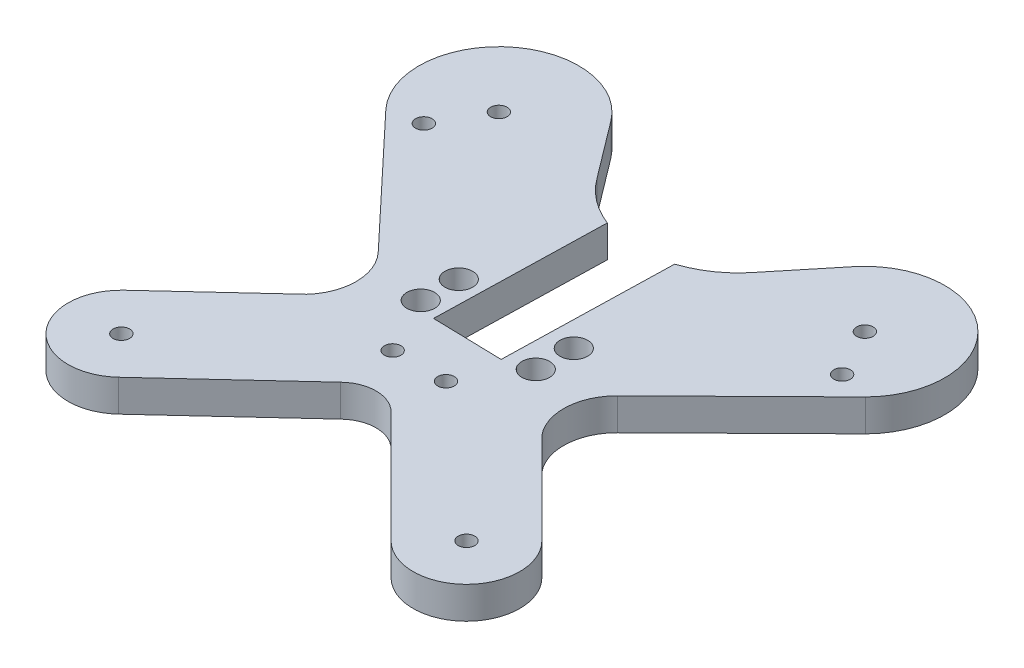
SolidWorks part; units mm, degrees
ref_plane "Płaszczyzna przednia" through (0, 0, 0) normal (0, 0, 1) x (1, 0, 0)
ref_plane "Płaszczyzna górna" through (0, 0, 0) normal (0, 1, 0) x (1, 0, 0)
ref_plane "Płaszczyzna prawa" through (0, 0, 0) normal (1, 0, 0) x (0, 0, -1)
sketch "Szkic13" plane through (79.2892, 6, 79.2892) normal (0, 1, 0) x (-1, 0, 0)
  line L0 (-25.2024, 55.7495) -> (-3.5513, 75.7828)
  line L3 (14.9337, 7.1523) -> (-7.5965, 31.1146)
  line L5 (-76.8088, 8.9318) -> (-53.3664, 32.0024)
  line L6 (-46.2432, -0.9711) -> (-54.4486, -11.0116)
  line L7 (-69.8185, 62.6517) -> (-52.6992, 45.5325)
  line L8 (10.0317, 61.1029) -> (-7.7385, 44.6604)
  line L9 (-34.8185, 55.936) -> (-55.6763, 76.7939)
  line L10 (-15.993, -1.5579) -> (-8.1832, -11.909)
  arc A0 (-30.9742, 6.1522) -> (-46.2432, -0.9711) centre (-31.6278, -12.3732) ccw
  arc A1 (-76.8088, 8.9318) -> (-54.4486, -11.0116) centre (-66.1313, -1.6033) ccw
  arc A4 (-53.3664, 32.0024) -> (-52.6992, 45.5325) centre (-60.3807, 39.1297) ccw
  arc A5 (-55.6763, 76.7939) -> (-69.8185, 62.6517) centre (-62.7474, 69.7228) ccw
  arc A8 (-25.2024, 55.7495) -> (-34.8185, 55.936) centre (-29.9171, 60.6508) cw
  circle A9 centre (-62.7474, 69.7228) radius 1.55
  circle A10 centre (3.8556, -2.9609) radius 1.55
  circle A11 centre (3.2402, 68.4429) radius 1.55
  arc A12 (-3.5513, 75.7828) -> (10.0317, 61.1029) centre (3.2402, 68.4429) cw
  arc A13 (-7.5965, 31.1146) -> (-7.7385, 44.6604) centre (-0.3111, 37.9646) cw
  arc A14 (14.9337, 7.1523) -> (-8.1832, -11.909) centre (3.8556, -2.9609) cw
  arc A15 (-30.9742, 6.1522) -> (-15.993, -1.5579) centre (-31.0396, -12.3846) cw
  circle A16 centre (-66.1313, -1.6033) radius 1.55
  point P0 (-30.04, 54.3163)
  point P8 (63.5409, 13.6837)
  point P13 (35.249, 13.1731)
  point P15 (48.4817, 2.8745)
  point P16 (62.1038, 12.6522)
  point P18 (25.4777, 4.012)
extrude "Dodanie-wyciągnięcie3" add sketch "Szkic13" along a picked direction on the side against the normal blind 6
sketch "Szkic15" plane through (0, 0, 0) normal (0, -1, 0) x (0.7071, 0, 0.7071)
  circle A0 centre (145.7265, 5.9479) radius 2.6 construction
  circle A2 centre (161.5816, -9.3039) radius 2.6 construction
  circle A3 centre (166.4344, -4.2591) radius 2.6 construction
  circle A8 centre (145.7265, 5.9479) radius 2.6
  circle A9 centre (150.5793, 10.9927) radius 2.6
  circle A10 centre (161.5816, -9.3039) radius 2.6
  circle A11 centre (166.4344, -4.2591) radius 2.6
extrude "Wytnij-wyciągnięcie3" cut sketch "Szkic15" against normal through all
sketch "Szkic16" plane through (0, 0, 0) normal (0, -1, 0) x (0.7071, 0, 0.7071)
  circle A0 centre (167.6028, -44.8757) radius 3 construction
  circle A1 centre (109.9479, 10.5852) radius 3 construction
  circle A2 centre (167.6028, -44.8757) radius 3
  circle A3 centre (109.9479, 10.5852) radius 3
  circle A4 centre (109.9479, 10.5852) radius 1.55
  circle A5 centre (167.6028, -44.8757) radius 1.55
  dimension "D1" = 3.1
  dimension "D2" = 3.1
sketch "Szkic17" plane through (0, 0, 0) normal (0, -1, 0) x (0.7071, 0, 0.7071)
  circle A0 centre (109.9479, 10.5852) radius 1.55 construction
  circle A1 centre (167.6028, -44.8757) radius 1.55 construction
  circle A2 centre (109.9479, 10.5852) radius 1.55
  circle A3 centre (167.6028, -44.8757) radius 1.55
extrude "Wytnij-wyciągnięcie4" cut sketch "Szkic17" against normal blind 10
move or copy body "Obiekt-Przenieś/Kopiuj1" bodies to move or copy 120 placed by mates yes
sketch "Szkic18" plane through (0, 0, 0) normal (0, -1, 0) x (1, 0, 0)
  line L0 (116.6227, 84.5531) -> (115.83, 116.3037)
  line L1 (115.83, 116.3037) -> (102.834, 115.9811)
  line L2 (102.834, 115.9811) -> (103.6183, 84.1843)
  arc A0 (125.5325, 78.3181) -> (110.2635, 85.4415) centre (110.917, 66.9161) ccw construction
  arc A1 (110.2635, 85.4415) -> (95.2822, 77.7314) centre (110.3288, 66.9047) ccw construction
  arc A2 (116.6227, 84.5531) -> (110.2635, 85.4415) centre (110.917, 66.9161) ccw
  arc A3 (110.2635, 85.4415) -> (103.6183, 84.1843) centre (110.3288, 66.9047) ccw
  point P0 (104.9725, 35.8595)
  point P2 (117.8223, 36.0284)
  point P4 (102.9877, 115.8349)
  point P7 (104.8263, 35.7058)
extrude "Wytnij-wyciągnięcie5" cut sketch "Szkic18" against normal blind 10
sketch "Szkic19" plane through (0, 0, 0) normal (0, -1, 0) x (1, 0, 0)
  line L0 (115.83, 116.3037) -> (102.834, 115.9811) construction
  circle A0 centre (104.2064, 125.018) radius 1.55
  circle A1 centre (114.2064, 125.018) radius 1.55
  arc A2 (104.4916, 135.0387) -> (114.1077, 135.2252) centre (109.2064, 139.94) ccw construction
  dimension "D1" = 3.1
  dimension "D2" = 3.1
  dimension "D3" = 10
  dimension "D4" = 9
  dimension "D5" = 5
extrude "Wytnij-wyciągnięcie6" cut sketch "Szkic19" against normal blind 10
equation "\"tolerancja_wpusy\"=0.2"
equation "\"dlugosc_wpustu_duzy\"=20"
equation "\"srednica_otworu_M3\"=3.1"
equation "\"szerokosc_nogi_T\"=3.1"
equation "\"dlugosc_T_30\"=11"
equation "\"grubosc_na_nakretke_kwadrat\"=2"
equation "\"szerokosc_na_nakretke_kwadrat\"=5.85"
equation "\"wyokosc_nadstawki_T\"=0.5"
equation "\"dlugosc_T_20_6\"=14"
equation "\"D1@Szkic16\"=\"srednica_otworu_M3\""
equation "\"D2@Szkic16\"=\"srednica_otworu_M3\""
